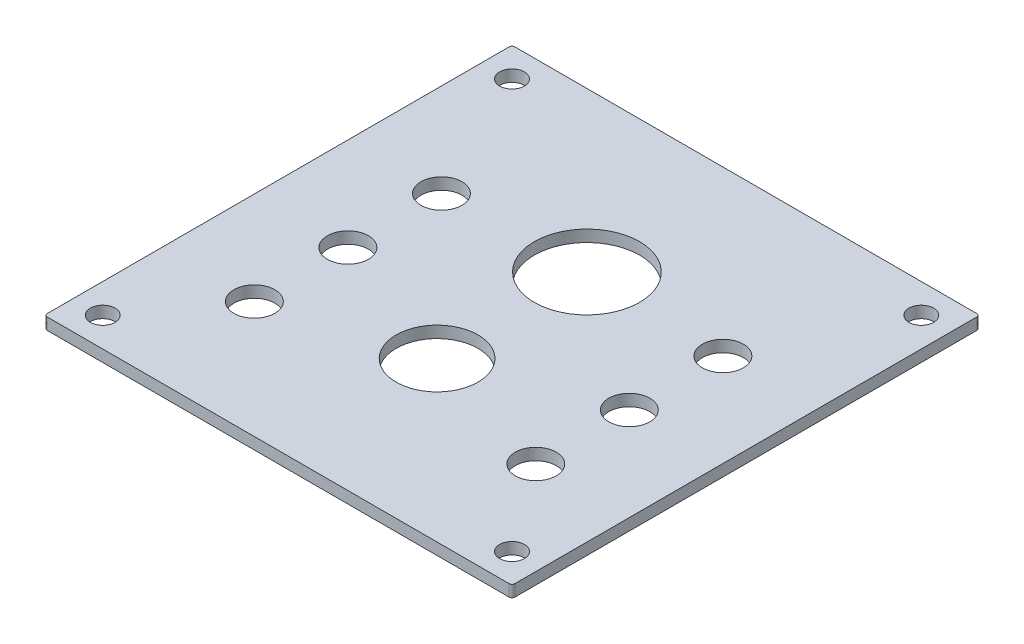
SolidWorks part; units mm, degrees
ref_plane "Front Plane" through (0, 0, 0) normal (0, 0, 1) x (1, 0, 0)
ref_plane "Top Plane" through (0, 0, 0) normal (0, 1, 0) x (1, 0, 0)
ref_plane "Right Plane" through (0, 0, 0) normal (1, 0, 0) x (0, 0, -1)
ref_plane "Plane1" through (0, -3.175, 0) normal (0, -1, 0) x (1, 0, 0)
sketch "Sketch1" plane through (0, -3.175, 0) normal (0, -1, 0) x (1, 0, 0)
  line L0 (76.3793, 48.6898) -> (-49.0332, 48.6898)
  line L1 (-49.8269, 47.896) -> (-49.8269, -77.5165)
  line L2 (-49.0332, -78.3102) -> (76.3793, -78.3102)
  line L3 (77.1731, -77.5165) -> (77.1731, 47.896)
  circle A0 centre (51.8813, -8.4602) radius 5.5626
  circle A1 centre (51.8813, -33.8602) radius 5.5626
  circle A2 centre (-24.5351, 16.9398) radius 5.5626
  circle A3 centre (-41.8894, 40.7523) radius 3.3528
  circle A4 centre (13.6731, 5.5352) radius 11.1125
  circle A5 centre (69.2356, -70.3727) radius 3.3528
  arc A6 (77.1731, 47.896) -> (76.3793, 48.6898) centre (76.3793, 47.896) ccw
  arc A7 (-49.0332, 48.6898) -> (-49.8269, 47.896) centre (-49.0332, 47.896) ccw
  arc A8 (-49.8269, -77.5165) -> (-49.0332, -78.3102) centre (-49.0332, -77.5165) ccw
  arc A9 (76.3793, -78.3102) -> (77.1731, -77.5165) centre (76.3793, -77.5165) ccw
  circle A10 centre (69.2356, 40.7523) radius 3.3528
  circle A11 centre (-41.8894, -70.3727) radius 3.3528
  circle A12 centre (13.6731, -35.1556) radius 14.2875
  circle A13 centre (-24.5351, -8.4602) radius 5.5626
  circle A14 centre (51.8813, 16.9398) radius 5.5626
  circle A15 centre (-24.5351, -33.8602) radius 5.5626
extrude "Boss-Extrude1" add sketch "Sketch1" against normal blind 3.175
